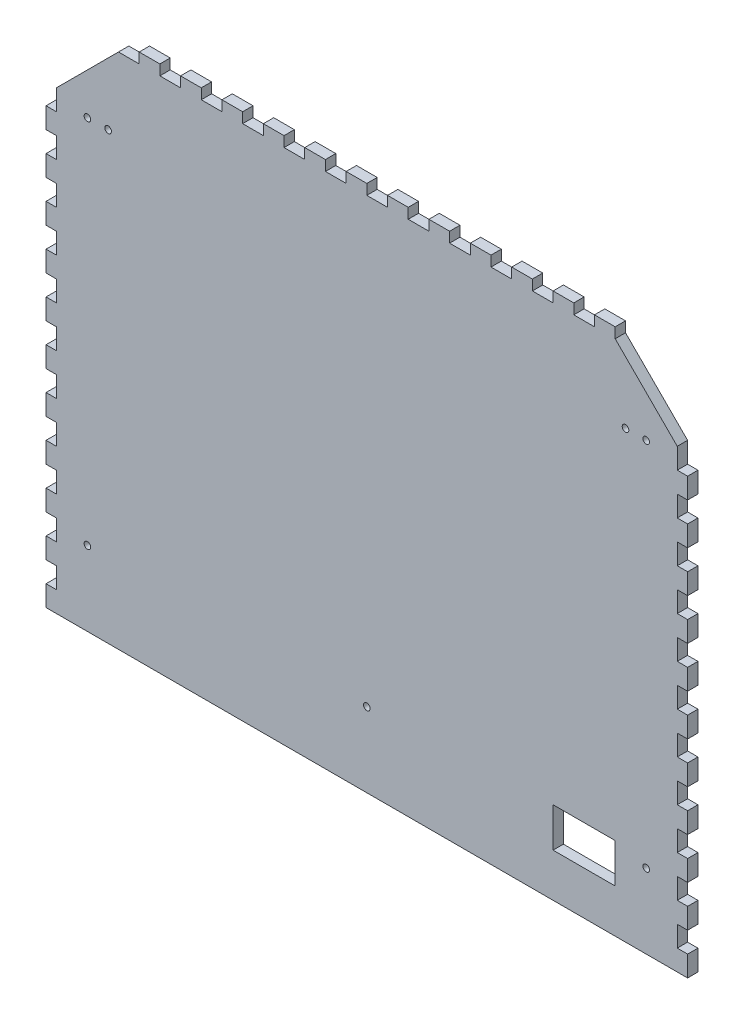
SolidWorks part; units mm, degrees
material "Buche"
ref_plane "Ebene vorne" through (0, 0, 0) normal (0, 0, 1) x (1, 0, 0)
ref_plane "Ebene oben" through (0, 0, 0) normal (0, 1, 0) x (1, 0, 0)
ref_plane "Ebene rechts" through (0, 0, 0) normal (1, 0, 0) x (0, 0, -1)
sketch "Skizze1" plane through (0, 0, 0) normal (0, 0, 1) x (1, 0, 0)
  line L0 (5, 10) -> (5, 20)
  line L1 (5, 0) -> (305, 0)
  line L2 (305, 10) -> (305, 20)
  line L3 (55, 250) -> (65, 250)
  line L4 (5, 220) -> (35, 250)
  line L5 (305, 220) -> (275, 250)
  line L6 (35, 250) -> (45, 250)
  line L7 (45, 250) -> (45, 255)
  line L8 (45, 255) -> (55, 255)
  line L9 (55, 255) -> (55, 250)
  line L10 (65, 250) -> (65, 255)
  line L11 (65, 255) -> (75, 255)
  line L12 (75, 255) -> (75, 250)
  line L13 (305, 0) -> (310, 0)
  line L14 (310, 0) -> (310, 10)
  line L15 (310, 10) -> (305, 10)
  line L16 (305, 30) -> (305, 40)
  line L17 (305, 20) -> (310, 20)
  line L18 (310, 20) -> (310, 30)
  line L19 (310, 30) -> (305, 30)
  line L20 (305, 50) -> (305, 60)
  line L21 (305, 40) -> (310, 40)
  line L22 (310, 40) -> (310, 50)
  line L23 (310, 50) -> (305, 50)
  line L24 (305, 70) -> (305, 80)
  line L25 (305, 60) -> (310, 60)
  line L26 (310, 60) -> (310, 70)
  line L27 (310, 70) -> (305, 70)
  line L28 (305, 90) -> (305, 100)
  line L29 (305, 80) -> (310, 80)
  line L30 (310, 80) -> (310, 90)
  line L31 (310, 90) -> (305, 90)
  line L32 (305, 110) -> (305, 120)
  line L33 (305, 100) -> (310, 100)
  line L34 (310, 100) -> (310, 110)
  line L35 (310, 110) -> (305, 110)
  line L36 (305, 130) -> (305, 140)
  line L37 (305, 120) -> (310, 120)
  line L38 (310, 120) -> (310, 130)
  line L39 (310, 130) -> (305, 130)
  line L40 (305, 150) -> (305, 160)
  line L41 (305, 140) -> (310, 140)
  line L42 (310, 140) -> (310, 150)
  line L43 (310, 150) -> (305, 150)
  line L44 (305, 170) -> (305, 180)
  line L45 (305, 160) -> (310, 160)
  line L46 (310, 160) -> (310, 170)
  line L47 (310, 170) -> (305, 170)
  line L48 (305, 190) -> (305, 200)
  line L49 (305, 180) -> (310, 180)
  line L50 (310, 180) -> (310, 190)
  line L51 (310, 190) -> (305, 190)
  line L52 (305, 210) -> (305, 220)
  line L53 (305, 200) -> (310, 200)
  line L54 (310, 200) -> (310, 210)
  line L55 (310, 210) -> (305, 210)
  line L56 (5, 0) -> (0, 0)
  line L57 (0, 0) -> (0, 10)
  line L58 (0, 10) -> (5, 10)
  line L59 (5, 30) -> (5, 40)
  line L60 (0, 20) -> (0, 30)
  line L61 (0, 30) -> (5, 30)
  line L62 (5, 50) -> (5, 60)
  line L63 (0, 40) -> (0, 50)
  line L64 (0, 50) -> (5, 50)
  line L65 (5, 70) -> (5, 80)
  line L66 (0, 60) -> (0, 70)
  line L67 (0, 70) -> (5, 70)
  line L68 (5, 90) -> (5, 100)
  line L69 (0, 80) -> (0, 90)
  line L70 (0, 90) -> (5, 90)
  line L71 (5, 110) -> (5, 120)
  line L72 (0, 100) -> (0, 110)
  line L73 (0, 110) -> (5, 110)
  line L74 (5, 130) -> (5, 140)
  line L75 (0, 120) -> (0, 130)
  line L76 (0, 130) -> (5, 130)
  line L77 (5, 150) -> (5, 160)
  line L78 (0, 140) -> (0, 150)
  line L79 (0, 150) -> (5, 150)
  line L80 (5, 170) -> (5, 180)
  line L81 (0, 160) -> (0, 170)
  line L82 (0, 170) -> (5, 170)
  line L83 (5, 190) -> (5, 200)
  line L84 (0, 180) -> (0, 190)
  line L85 (0, 190) -> (5, 190)
  line L86 (5, 210) -> (5, 220)
  line L87 (0, 200) -> (0, 210)
  line L88 (0, 210) -> (5, 210)
  line L89 (0, 20) -> (5, 20)
  line L90 (0, 40) -> (5, 40)
  line L91 (0, 60) -> (5, 60)
  line L92 (0, 80) -> (5, 80)
  line L93 (0, 100) -> (5, 100)
  line L94 (0, 120) -> (5, 120)
  line L95 (0, 140) -> (5, 140)
  line L96 (0, 160) -> (5, 160)
  line L97 (0, 180) -> (5, 180)
  line L98 (0, 200) -> (5, 200)
  line L99 (75, 250) -> (85, 250)
  line L100 (85, 250) -> (85, 255)
  line L101 (85, 255) -> (95, 255)
  line L102 (95, 255) -> (95, 250)
  line L103 (95, 250) -> (105, 250)
  line L104 (105, 250) -> (105, 255)
  line L105 (105, 255) -> (115, 255)
  line L106 (115, 255) -> (115, 250)
  line L107 (115, 250) -> (125, 250)
  line L108 (125, 250) -> (125, 255)
  line L109 (125, 255) -> (135, 255)
  line L110 (135, 255) -> (135, 250)
  line L111 (135, 250) -> (145, 250)
  line L112 (145, 250) -> (145, 255)
  line L113 (145, 255) -> (155, 255)
  line L114 (155, 255) -> (155, 250)
  line L115 (155, 250) -> (165, 250)
  line L116 (165, 250) -> (165, 255)
  line L117 (165, 255) -> (175, 255)
  line L118 (175, 255) -> (175, 250)
  line L119 (175, 250) -> (185, 250)
  line L120 (185, 250) -> (185, 255)
  line L121 (185, 255) -> (195, 255)
  line L122 (195, 255) -> (195, 250)
  line L123 (195, 250) -> (205, 250)
  line L124 (205, 250) -> (205, 255)
  line L125 (205, 255) -> (215, 255)
  line L126 (215, 255) -> (215, 250)
  line L127 (215, 250) -> (225, 250)
  line L128 (225, 250) -> (225, 255)
  line L129 (225, 255) -> (235, 255)
  line L130 (235, 255) -> (235, 250)
  line L131 (235, 250) -> (245, 250)
  line L132 (245, 250) -> (245, 255)
  line L133 (245, 255) -> (255, 255)
  line L134 (255, 255) -> (255, 250)
  line L135 (255, 250) -> (265, 250)
  line L136 (265, 250) -> (265, 255)
  line L137 (265, 255) -> (275, 255)
  line L138 (275, 255) -> (275, 250)
  line L140 (245, 21) -> (275, 21)
  line L141 (245, 21) -> (245, 40)
  line L142 (245, 40) -> (275, 40)
  line L143 (275, 21) -> (275, 40)
  circle A0 centre (20, 215) radius 1.6
  circle A1 centre (30, 215) radius 1.6
  circle A2 centre (290, 215) radius 1.6
  circle A3 centre (280, 215) radius 1.6
  circle A4 centre (20, 36) radius 1.6
  circle A5 centre (155, 36) radius 1.6
  circle A6 centre (290, 36) radius 1.6
  dimension "D1" = 12
extrude "Aufsatz-Linear austragen1" add sketch "Skizze1" along normal blind 5
